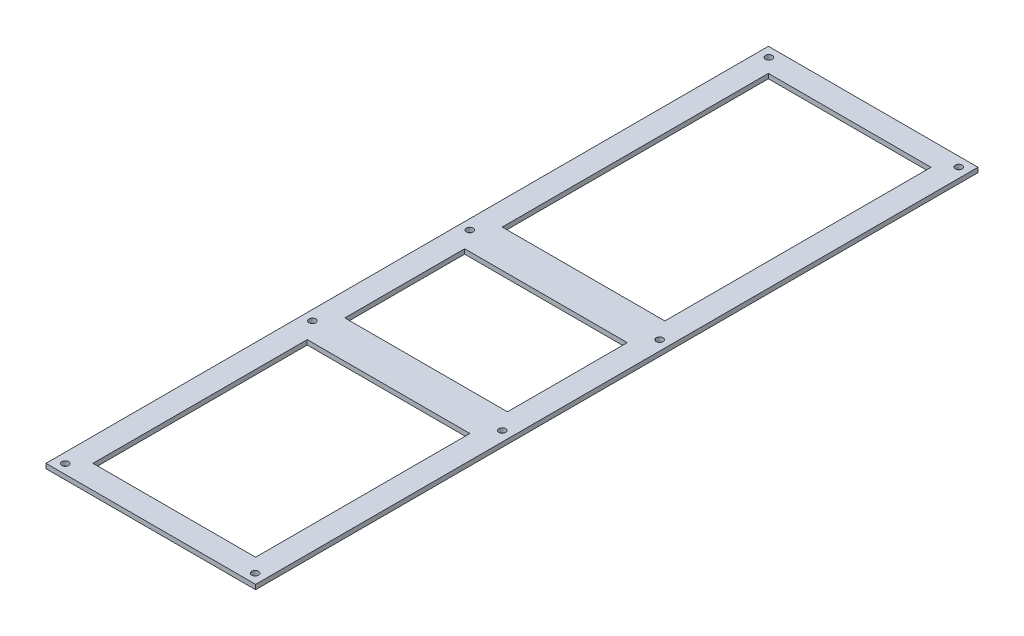
SolidWorks part; units mm, degrees
material "6061 Alloy"
ref_plane "Front Plane" through (0, 0, 0) normal (0, 0, 1) x (1, 0, 0)
ref_plane "Top Plane" through (0, 0, 0) normal (0, 1, 0) x (1, 0, 0)
ref_plane "Right Plane" through (0, 0, 0) normal (1, 0, 0) x (0, 0, -1)
sketch "Sketch1" plane through (0, 0, 0) normal (0, 1, 0) x (1, 0, 0)
  line L0 (10, 0) -> (10, 27.8) construction
  line L1 (0, 0) -> (89.225, 0)
  line L2 (0, 0) -> (0, 307.5)
  line L3 (0, 307.5) -> (89.225, 307.5)
  line L4 (89.225, 0) -> (89.225, 307.5)
  line L5 (79.225, 307.5) -> (79.225, 283.2) construction
  line L7 (10, 10) -> (79.225, 10)
  line L8 (10, 10) -> (10, 21.8)
  line L10 (79.225, 10) -> (79.225, 21.8)
  line L24 (10, 81.2) -> (10, 101.2)
  line L25 (10, 101.2) -> (79.225, 101.2)
  line L26 (79.225, 81.2) -> (79.225, 101.2)
  line L27 (10, 117.2) -> (79.225, 117.2)
  line L28 (10, 117.2) -> (10, 168.2)
  line L29 (10, 168.2) -> (79.225, 168.2)
  line L30 (79.225, 117.2) -> (79.225, 168.2)
  line L31 (10, 297.5) -> (79.225, 297.5)
  line L32 (10, 297.5) -> (10, 283.2)
  line L33 (10, 184.2) -> (79.225, 184.2)
  line L34 (79.225, 297.5) -> (79.225, 283.2)
  line L35 (56.6125, 10) -> (56.6125, 11) construction
  line L36 (32.6125, 10) -> (32.6125, 11) construction
  line L53 (10, 81.2) -> (10, 209.2) construction
  line L54 (79.225, 21.8) -> (79.225, 0) construction
  line L55 (10, 21.8) -> (10, 81.2)
  line L56 (79.225, 81.2) -> (79.225, 21.8)
  line L61 (10, 209.2) -> (10, 283.2)
  line L62 (79.225, 283.2) -> (79.225, 209.2)
  line L76 (79.225, 209.2) -> (79.225, 81.2) construction
  line L77 (79.225, 209.2) -> (79.225, 184.2)
  line L78 (10, 209.2) -> (10, 184.2)
  line L82 (10, 283.2) -> (10, 307.5) construction
  dimension "D1" = 307.5
  dimension "D2" = 89.225
  dimension "D3" = 10
  dimension "D4" = 10
  dimension "D5" = 10
  dimension "D11" = 10
  dimension "D12" = 16
  dimension "D13" = 16
  dimension "D15" = 83
  dimension "D16" = 24
extrude "Boss-Extrude1" add sketch "Sketch1" along normal blind 2
sketch "Sketch12" plane through (0, 0, 0) normal (0, 1, 0) x (1, 0, 0)
  line L0 (44.6125, 10) -> (44.6125, 75.2) construction
  line L1 (10, 10) -> (79.225, 10) construction
  line L2 (79.225, 75.2) -> (10, 75.2) construction
  line L3 (52.6125, 10) -> (52.6125, 75.2) construction
  line L4 (36.6125, 10) -> (36.6125, 75.2) construction
  line L5 (79.225, 57.4) -> (10, 57.4) construction
  line L6 (52.6125, 75.2) -> (36.6125, 75.2)
  line L7 (52.6125, 75.2) -> (52.6125, 74.2)
  line L8 (52.6125, 74.2) -> (36.6125, 74.2)
  line L9 (36.6125, 75.2) -> (36.6125, 74.2)
  line L10 (52.6125, 57.4) -> (36.6125, 57.4)
  line L11 (52.6125, 57.4) -> (52.6125, 56.4)
  line L12 (52.6125, 56.4) -> (36.6125, 56.4)
  line L13 (36.6125, 57.4) -> (36.6125, 56.4)
  line L14 (79.225, 39.6) -> (10, 39.6) construction
  line L15 (52.6125, 39.6) -> (36.6125, 39.6)
  line L16 (52.6125, 39.6) -> (52.6125, 38.6)
  line L17 (52.6125, 38.6) -> (36.6125, 38.6)
  line L18 (36.6125, 39.6) -> (36.6125, 38.6)
  line L19 (79.225, 21.8) -> (10, 21.8) construction
  line L20 (52.6125, 21.8) -> (36.6125, 21.8)
  line L21 (52.6125, 21.8) -> (52.6125, 20.8)
  line L22 (52.6125, 20.8) -> (36.6125, 20.8)
  line L23 (36.6125, 21.8) -> (36.6125, 20.8)
  dimension "D1" = 16
  dimension "D2" = 1
extrude "Boss-Extrude3" [suppressed] add sketch "Sketch12" along normal blind 2
sketch "Sketch13" [suppressed] plane through (0, 0, 0) normal (0, 1, 0) x (1, 0, 0)
  line L1 (52.6125, 74.2) -> (36.6125, 74.2)
  line L2 (52.6125, 74.2) -> (52.6125, 72.2)
  line L3 (52.6125, 72.2) -> (36.6125, 72.2)
  line L4 (36.6125, 74.2) -> (36.6125, 72.2)
  line L5 (52.6125, 56.4) -> (36.6125, 56.4)
  line L6 (52.6125, 56.4) -> (52.6125, 54.4)
  line L7 (52.6125, 54.4) -> (36.6125, 54.4)
  line L8 (36.6125, 56.4) -> (36.6125, 54.4)
  line L9 (52.6125, 38.6) -> (36.6125, 38.6)
  line L10 (52.6125, 38.6) -> (52.6125, 36.6)
  line L11 (52.6125, 36.6) -> (36.6125, 36.6)
  line L12 (36.6125, 38.6) -> (36.6125, 36.6)
  line L13 (52.6125, 20.8) -> (36.6125, 20.8)
  line L14 (52.6125, 20.8) -> (52.6125, 18.8)
  line L15 (52.6125, 18.8) -> (36.6125, 18.8)
  line L16 (36.6125, 20.8) -> (36.6125, 18.8)
  dimension "D1" = 2
extrude "Boss-Extrude4" [suppressed] add sketch "Sketch13" along normal blind 10
hole_wizard "M2.5 Clearance Hole1" [suppressed] positions "Sketch14" profile "Sketch15" hole size "M2.5" standard "ANSI Metric"
sketch "Sketch14" [suppressed] plane through (0, 0, -18.8) normal (0, 0, 1) x (1, 0, 0)
  line L0 (36.6125, 10) -> (52.6125, 10) construction
  point P0 (44.6125, 7.5)
  point P6 (44.6125, 10)
  dimension "D1" = 2.5
sketch "Sketch15" plane through (44.6125, 7.5, -18.8) normal (1, 0, 0) x (0, -1, 0)
  line L0 (0, 0) -> (0, 56.2702)
  line L1 (0, 56.2702) -> (1.45, 55.399)
  line L2 (1.45, 55.399) -> (1.45, 0)
  line L5 (1.45, 0) -> (0, 0)
  line L10 (0, 56.2702) -> (-1.45, 55.399) construction
  line L11 (0, -6.35) -> (0, 107.95) construction
  dimension "Hole Dia." = 2.9
  dimension "Hole Depth" = 55.399
  dimension "Drill Angle" = 118
sketch "Sketch16" [suppressed] plane through (0, 0, 0) normal (0, 1, 0) x (1, 0, 0)
  line L0 (65.4125, 101.2) -> (65.4125, 81.2) construction
  line L1 (79.225, 101.2) -> (10, 101.2) construction
  line L2 (10, 81.2) -> (79.225, 81.2) construction
  line L3 (23.8125, 101.2) -> (23.8125, 81.2) construction
  line L4 (79.225, 81.2) -> (79.225, 101.2) construction
  line L5 (10, 101.2) -> (10, 81.2) construction
  line L6 (10, 184.2) -> (79.225, 184.2) construction
  line L7 (70.4125, 101.2) -> (60.4125, 101.2)
  line L8 (70.4125, 101.2) -> (70.4125, 100.2)
  line L9 (70.4125, 100.2) -> (60.4125, 100.2)
  line L10 (60.4125, 101.2) -> (60.4125, 100.2)
  line L11 (28.8125, 101.2) -> (18.8125, 101.2)
  line L12 (28.8125, 101.2) -> (28.8125, 100.2)
  line L13 (28.8125, 100.2) -> (18.8125, 100.2)
  line L14 (18.8125, 101.2) -> (18.8125, 100.2)
  line L15 (70.4125, 184.2) -> (60.4125, 184.2)
  line L16 (70.4125, 184.2) -> (70.4125, 185.2)
  line L17 (70.4125, 185.2) -> (60.4125, 185.2)
  line L18 (60.4125, 184.2) -> (60.4125, 185.2)
  line L20 (28.8125, 184.2) -> (18.8125, 184.2)
  line L21 (28.8125, 184.2) -> (28.8125, 185.2)
  line L22 (28.8125, 185.2) -> (18.8125, 185.2)
  line L23 (18.8125, 184.2) -> (18.8125, 185.2)
  dimension "D1" = 13.8125
  dimension "D2" = 13.8125
  dimension "D3" = 1
  dimension "D4" = 10
  dimension "D5" = 1
extrude "Boss-Extrude5" [suppressed] add sketch "Sketch16" along normal blind 2
sketch "Sketch17" [suppressed] plane through (0, 0, 0) normal (0, 1, 0) x (1, 0, 0)
  line L1 (70.4125, 100.2) -> (60.4125, 100.2)
  line L2 (70.4125, 100.2) -> (70.4125, 98.2)
  line L3 (70.4125, 98.2) -> (60.4125, 98.2)
  line L4 (60.4125, 100.2) -> (60.4125, 98.2)
  line L5 (28.8125, 100.2) -> (18.8125, 100.2)
  line L6 (28.8125, 100.2) -> (28.8125, 98.2)
  line L7 (28.8125, 98.2) -> (18.8125, 98.2)
  line L8 (18.8125, 100.2) -> (18.8125, 98.2)
  line L9 (70.4125, 185.2) -> (60.4125, 185.2)
  line L10 (70.4125, 185.2) -> (70.4125, 187.2)
  line L11 (70.4125, 187.2) -> (60.4125, 187.2)
  line L12 (60.4125, 185.2) -> (60.4125, 187.2)
  line L13 (28.8125, 185.2) -> (18.8125, 185.2)
  line L14 (28.8125, 185.2) -> (28.8125, 187.2)
  line L15 (28.8125, 187.2) -> (18.8125, 187.2)
  line L16 (18.8125, 185.2) -> (18.8125, 187.2)
  dimension "D1" = 2
  dimension "D2" = 2
extrude "Boss-Extrude6" [suppressed] add sketch "Sketch17" along normal blind 12
fillet "Fillet3" [suppressed] radius 2
fillet "Fillet4" [suppressed] radius 1
fillet "Fillet5" [suppressed] radius 1
fillet "Fillet6" [suppressed] radius 2
hole_wizard "M2.5 Clearance Hole2" [suppressed] positions "Sketch18" profile "Sketch19" hole size "M2.5" standard "ANSI Metric"
sketch "Sketch18" plane through (0, 0, -187.2) normal (0, 0, -1) x (-1, 0, 0)
  line L0 (-70.4125, 12) -> (-60.4125, 12) construction
  line L2 (-28.8125, 12) -> (-18.8125, 12) construction
  point P0 (-65.4125, 9.5)
  point P2 (-23.8125, 9.5)
  point P11 (-65.4125, 12)
  point P14 (-23.8125, 12)
  dimension "D1" = 2.5
sketch "Sketch19" plane through (65.4125, 9.5, -187.2) normal (1, 0, 0) x (0, 1, 0)
  line L0 (0, 0) -> (0, 89.8702)
  line L1 (0, 89.8702) -> (1.45, 88.999)
  line L2 (1.45, 88.999) -> (1.45, 0)
  line L5 (1.45, 0) -> (0, 0)
  line L10 (0, 89.8702) -> (-1.45, 88.999) construction
  line L11 (0, -6.35) -> (0, 107.95) construction
  dimension "Hole Dia." = 2.9
  dimension "Hole Depth" = 88.999
  dimension "Drill Angle" = 118
sketch "Sketch20" plane through (0, 0, 0) normal (0, 1, 0) x (1, 0, 0)
  line L0 (10, 184.2) -> (79.225, 184.2) construction
  line L1 (44.7, 184.2) -> (22.7, 184.2)
  line L2 (44.7, 184.2) -> (44.7, 185.2)
  line L3 (44.7, 185.2) -> (22.7, 185.2)
  line L4 (22.7, 184.2) -> (22.7, 185.2)
  line L6 (10, 297.5) -> (10, 184.2) construction
  point P6 (33.7, 184.2)
  dimension "D1" = 23.7
  dimension "D2" = 22
  dimension "D3" = 1
extrude "Boss-Extrude7" [suppressed] add sketch "Sketch20" along normal blind 2
sketch "Sketch21" [suppressed] plane through (0, 0, 0) normal (0, 1, 0) x (1, 0, 0)
  line L1 (44.7, 185.2) -> (22.7, 185.2)
  line L2 (44.7, 185.2) -> (44.7, 187.2)
  line L3 (44.7, 187.2) -> (22.7, 187.2)
  line L4 (22.7, 185.2) -> (22.7, 187.2)
  dimension "D1" = 2
extrude "Boss-Extrude8" [suppressed] add sketch "Sketch21" along normal blind 12
fillet "Fillet7" [suppressed] radius 2
fillet "Fillet8" [suppressed] radius 1
hole_wizard "M2.5 Clearance Hole3" [suppressed] positions "Sketch22" profile "Sketch23" hole size "M2.5" standard "ANSI Metric"
sketch "Sketch22" [suppressed] plane through (0, 0, -185.2) normal (0, 0, 1) x (1, 0, 0)
  line L0 (22.7, 12) -> (44.7, 12) construction
  point P0 (33.7, 7.4125)
  point P5 (33.7, 12)
  dimension "D1" = 4.5875
sketch "Sketch23" plane through (33.7, 7.4125, -185.2) normal (1, 0, 0) x (0, -1, 0)
  line L0 (0, 0) -> (0, 2.8702)
  line L1 (0, 2.8702) -> (1.45, 1.999)
  line L2 (1.45, 1.999) -> (1.45, 0)
  line L5 (1.45, 0) -> (0, 0)
  line L10 (0, 2.8702) -> (-1.45, 1.999) construction
  line L11 (0, -6.35) -> (0, 107.95) construction
  dimension "Hole Dia." = 2.9
  dimension "Hole Depth" = 1.999
  dimension "Drill Angle" = 118
sketch "Sketch24" [suppressed] plane through (0, 0, 0) normal (0, 1, 0) x (1, 0, 0)
  line L0 (10, 184.2) -> (79.225, 184.2) construction
  line L1 (66.525, 184.2) -> (44.525, 184.2)
  line L2 (66.525, 184.2) -> (66.525, 185.2)
  line L3 (66.525, 185.2) -> (44.525, 185.2)
  line L4 (44.525, 184.2) -> (44.525, 185.2)
  line L5 (79.225, 283.2) -> (79.225, 297.5) construction
  point P6 (55.525, 184.2)
  dimension "D1" = 23.7
  dimension "D2" = 22
  dimension "D3" = 1
extrude "Boss-Extrude9" [suppressed] add sketch "Sketch24" along normal blind 2
sketch "Sketch25" [suppressed] plane through (0, 0, 0) normal (0, 1, 0) x (1, 0, 0)
  line L1 (66.525, 185.2) -> (44.525, 185.2)
  line L2 (66.525, 185.2) -> (66.525, 187.2)
  line L3 (66.525, 187.2) -> (44.525, 187.2)
  line L4 (44.525, 185.2) -> (44.525, 187.2)
  dimension "D1" = 2
extrude "Boss-Extrude10" [suppressed] add sketch "Sketch25" along normal blind 12
hole_wizard "M2.5 Clearance Hole4" [suppressed] positions "Sketch26" profile "Sketch27" hole size "M2.5" standard "ANSI Metric"
sketch "Sketch26" plane through (0, 0, -187.2) normal (0, 0, -1) x (-1, 0, 0)
  line L0 (-66.525, 12) -> (-44.525, 12) construction
  point P0 (-55.525, 7.4125)
  point P7 (-55.525, 12)
  dimension "D1" = 4.5875
sketch "Sketch27" plane through (55.525, 7.4125, -187.2) normal (1, 0, 0) x (0, 1, 0)
  line L0 (0, 0) -> (0, 2.8712)
  line L1 (0, 2.8712) -> (1.45, 2)
  line L2 (1.45, 2) -> (1.45, 0)
  line L5 (1.45, 0) -> (0, 0)
  line L10 (0, 2.8712) -> (-1.45, 2) construction
  line L11 (0, -6.35) -> (0, 107.95) construction
  dimension "Hole Dia." = 2.9
  dimension "Hole Depth" = 2
  dimension "Drill Angle" = 118
fillet "Fillet9" [suppressed] radius 1
fillet "Fillet10" [suppressed] radius 2
sketch "Sketch28" plane through (0, 0, 0) normal (0, 1, 0) x (1, 0, 0)
  line L0 (79.225, 209.2) -> (10, 209.2) construction
  line L1 (72.6125, 209.2) -> (60.6125, 209.2)
  line L2 (72.6125, 209.2) -> (72.6125, 208.2)
  line L3 (72.6125, 208.2) -> (60.6125, 208.2)
  line L4 (60.6125, 209.2) -> (60.6125, 208.2)
  line L5 (10, 283.2) -> (79.225, 283.2) construction
  line L6 (50.6125, 209.2) -> (38.6125, 209.2)
  line L7 (50.6125, 209.2) -> (50.6125, 208.2)
  line L8 (50.6125, 208.2) -> (38.6125, 208.2)
  line L9 (38.6125, 209.2) -> (38.6125, 208.2)
  line L10 (28.6125, 209.2) -> (16.6125, 209.2)
  line L11 (28.6125, 209.2) -> (28.6125, 208.2)
  line L12 (28.6125, 208.2) -> (16.6125, 208.2)
  line L13 (16.6125, 209.2) -> (16.6125, 208.2)
  line L14 (72.6125, 283.2) -> (60.6125, 283.2)
  line L15 (72.6125, 283.2) -> (72.6125, 284.2)
  line L16 (72.6125, 284.2) -> (60.6125, 284.2)
  line L17 (60.6125, 283.2) -> (60.6125, 284.2)
  line L18 (72.6125, 283.2) -> (79.225, 283.2) construction
  line L19 (50.6125, 283.2) -> (38.6125, 283.2)
  line L20 (50.6125, 283.2) -> (50.6125, 284.2)
  line L21 (50.6125, 284.2) -> (38.6125, 284.2)
  line L22 (38.6125, 283.2) -> (38.6125, 284.2)
  line L23 (28.6125, 283.2) -> (16.6125, 283.2)
  line L24 (28.6125, 283.2) -> (28.6125, 284.2)
  line L25 (28.6125, 284.2) -> (16.6125, 284.2)
  line L26 (16.6125, 283.2) -> (16.6125, 284.2)
  line L27 (16.6125, 283.2) -> (10, 283.2) construction
  dimension "D1" = 1
  dimension "D2" = 1
  dimension "D3" = 10
  dimension "D4" = 10
  dimension "D5" = 12
extrude "Boss-Extrude11" [suppressed] add sketch "Sketch28" along normal blind 2
sketch "Sketch29" [suppressed] plane through (0, 0, 0) normal (0, 1, 0) x (1, 0, 0)
  line L0 (16.6125, 208.2) -> (28.6125, 208.2) construction
  line L1 (72.6125, 208.2) -> (60.6125, 208.2)
  line L2 (72.6125, 208.2) -> (72.6125, 206.2)
  line L3 (72.6125, 206.2) -> (60.6125, 206.2)
  line L4 (60.6125, 208.2) -> (60.6125, 206.2)
  line L5 (50.6125, 208.2) -> (38.6125, 208.2)
  line L6 (50.6125, 208.2) -> (50.6125, 206.2)
  line L7 (50.6125, 206.2) -> (38.6125, 206.2)
  line L8 (38.6125, 208.2) -> (38.6125, 206.2)
  line L9 (28.6125, 208.2) -> (16.6125, 208.2)
  line L10 (28.6125, 208.2) -> (28.6125, 206.2)
  line L11 (28.6125, 206.2) -> (16.6125, 206.2)
  line L12 (16.6125, 208.2) -> (16.6125, 206.2)
  line L13 (72.6125, 284.2) -> (60.6125, 284.2)
  line L14 (72.6125, 284.2) -> (72.6125, 286.2)
  line L15 (72.6125, 286.2) -> (60.6125, 286.2)
  line L16 (60.6125, 284.2) -> (60.6125, 286.2)
  line L17 (50.6125, 284.2) -> (38.6125, 284.2)
  line L18 (50.6125, 284.2) -> (50.6125, 286.2)
  line L19 (50.6125, 286.2) -> (38.6125, 286.2)
  line L20 (38.6125, 284.2) -> (38.6125, 286.2)
  line L21 (28.6125, 284.2) -> (16.6125, 284.2)
  line L22 (28.6125, 284.2) -> (28.6125, 286.2)
  line L23 (28.6125, 286.2) -> (16.6125, 286.2)
  line L24 (16.6125, 284.2) -> (16.6125, 286.2)
  dimension "D1" = 2
extrude "Boss-Extrude12" [suppressed] add sketch "Sketch29" along normal blind 12
fillet "Fillet11" [suppressed] radius 2
fillet "Fillet12" [suppressed] radius 1
hole_wizard "M2.5 Clearance Hole5" [suppressed] positions "Sketch30" profile "Sketch32" hole size "M2.5" standard "ANSI Metric"
sketch "Sketch30" [suppressed] plane through (0, 0, -286.2) normal (0, 0, -1) x (-1, 0, 0)
  line L0 (-72.6125, 12) -> (-60.6125, 12) construction
  line L1 (-50.6125, 12) -> (-38.6125, 12) construction
  line L2 (-28.6125, 12) -> (-16.6125, 12) construction
  point P0 (-66.6125, 9.5)
  point P2 (-44.6125, 9.5)
  point P4 (-22.6125, 9.5)
  point P10 (-66.6125, 12)
  point P13 (-44.6125, 12)
  point P18 (-22.6125, 12)
  dimension "D1" = 2.5
sketch "Sketch32" plane through (66.6125, 9.5, -286.2) normal (1, 0, 0) x (0, 1, 0)
  line L0 (0, 0) -> (0, 80.8702)
  line L1 (0, 80.8702) -> (1.45, 79.999)
  line L2 (1.45, 79.999) -> (1.45, 0)
  line L5 (1.45, 0) -> (0, 0)
  line L10 (0, 80.8702) -> (-1.45, 79.999) construction
  line L11 (0, -6.35) -> (0, 107.95) construction
  dimension "Hole Dia." = 2.9
  dimension "Hole Depth" = 79.999
  dimension "Drill Angle" = 118
hole_wizard "M2.5 Clearance Hole6" positions "Sketch33" profile "Sketch35" hole size "M2.5" standard "ANSI Metric" end condition through all
sketch "Sketch33" plane through (0, 2, 0) normal (0, 1, 0) x (1, 0, 0)
  line L0 (79.225, 10) -> (79.225, 101.2) construction
  line L1 (0, 0) -> (89.225, 0) construction
  line L2 (89.225, 307.5) -> (0, 307.5) construction
  line L3 (79.225, 168.2) -> (79.225, 184.2) construction
  line L5 (79.225, 101.2) -> (79.225, 117.2) construction
  line L7 (10, 101.2) -> (10, 10) construction
  point P0 (85.025, 4)
  point P2 (4.2, 4)
  point P4 (4.2, 109.2)
  point P6 (4.2, 176.2)
  point P8 (4.2, 303.5)
  point P10 (85.025, 303.5)
  point P12 (85.025, 176.2)
  point P14 (85.025, 109.2)
  point P33 (79.225, 176.2)
  point P40 (79.225, 109.2)
  dimension "D1" = 5.8
  dimension "D2" = 4
  dimension "D3" = 4
  dimension "D4" = 5.8
sketch "Sketch35" plane through (85.025, 2, -4) normal (1, 0, 0) x (0, 0, 1)
  line L0 (0, 0) -> (0, 2)
  line L1 (0, 2) -> (1.45, 2)
  line L2 (1.45, 2) -> (1.45, 0)
  line L5 (1.45, 0) -> (0, 0)
  line L11 (0, -6.35) -> (0, 107.95) construction
  dimension "Thru Hole Dia." = 2.9
  dimension "Thru Hole Depth" = 2
hole_wizard "M2 Clearance Hole1" positions "Sketch36" profile "Sketch37" hole size "M2" standard "ANSI Metric"
sketch "Sketch36" plane through (0, 0, 0) normal (0, -1, 0) x (-1, 0, 0)
  point P0 (-44.6125, 24.8)
  point P3 (-44.6125, 42.9)
  point P6 (-44.6125, 60.4)
  point P9 (-44.6125, 78.2)
sketch "Sketch37" plane through (44.6125, 0, -24.8) normal (1, 0, 0) x (0, 0, -1)
  line L0 (0, 0) -> (0, 2)
  line L1 (0, 2) -> (1.2, 2)
  line L2 (1.2, 2) -> (1.2, 0)
  line L5 (1.2, 0) -> (0, 0)
  line L11 (0, -6.35) -> (0, 107.95) construction
  dimension "Thru Hole Dia." = 2.4
  dimension "Thru Hole Depth" = 2
ref_plane "Plane1" [suppressed] through (-1, 0, 0) normal (-1, 0, 0) x (0, 0, 1)
